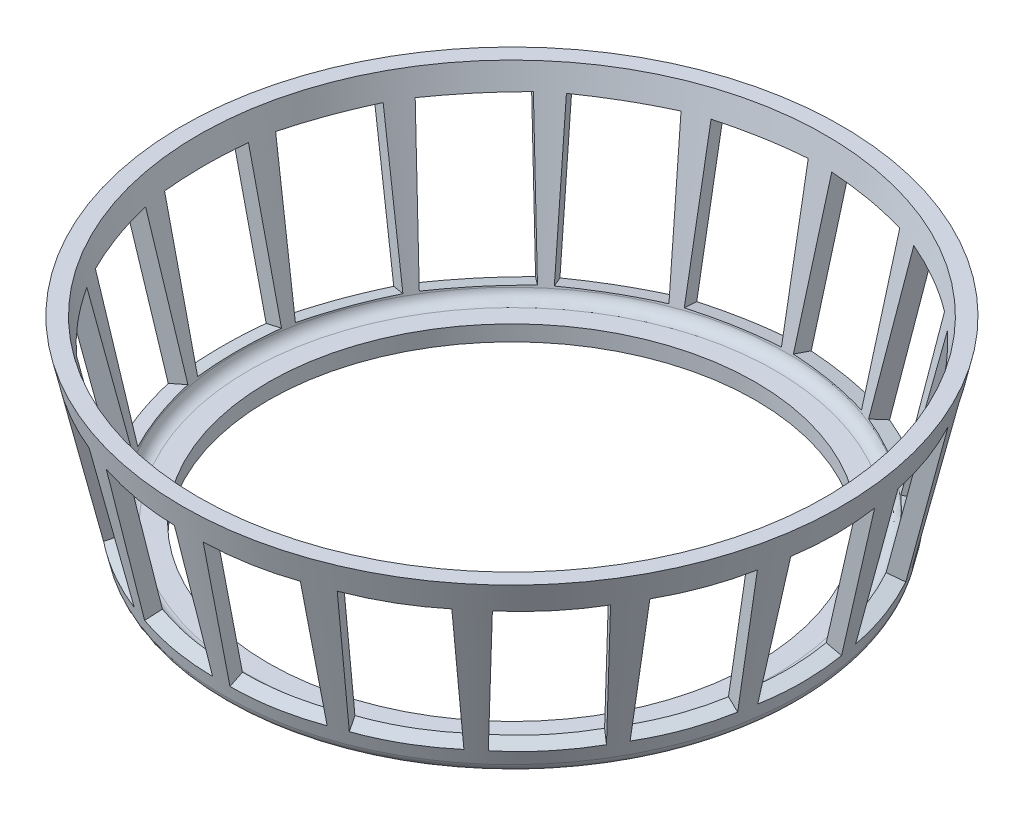
SolidWorks part; units mm, degrees
ref_plane "Front Plane" through (0, 0, 0) normal (0, 0, 1) x (1, 0, 0)
ref_plane "Top Plane" through (0, 0, 0) normal (0, 1, 0) x (1, 0, 0)
ref_plane "Right Plane" through (0, 0, 0) normal (1, 0, 0) x (0, 0, -1)
sketch "Sketch1" plane through (0, 0, 0) normal (0, 0, 1) x (1, 0, 0)
  line L0 (0, 12.1772) -> (0, 0) construction
  line L1 (0, 0) -> (-23.8186, 0) construction
  line L2 (-27.5, 16.23) -> (-23.9952, 0.7788)
  line L3 (-23.02, 0) -> (-20.3186, 0)
  line L4 (-26.167, 16.23) -> (-22.9571, 2.0788)
  line L5 (-21.9819, 1.3) -> (-20.3186, 1.3)
  line L6 (-27.5, 16.23) -> (-26.167, 16.23)
  line L7 (-20.3186, 1.3) -> (-20.3186, 0)
  line L8 (-26.2322, 16.5176) -> (-22.7804, 1.3) construction
  line L9 (-22.7804, 1.3) -> (-20.3186, 1.3) construction
  arc A0 (-23.02, 0) -> (-23.9952, 0.7788) centre (-23.02, 1) cw
  arc A2 (-22.9571, 2.0788) -> (-21.9819, 1.3) centre (-21.9819, 2.3) ccw
  arc A3 (-22.7804, 1.3) -> (-22.7804, 1.3) centre (-22.7804, 1.3) cw construction
  dimension "D5" = 1
  dimension "D7" = 1
  dimension "D1" = 27.5
  dimension "D2" = 102.78
  dimension "D3" = 3.5
  dimension "D4" = 16.23
  dimension "D6" = 1.3
revolve "Revolve1" add sketch "Sketch1" angle 360 about L0
sketch "Sketch2" plane through (0, 0, 0) normal (0, 0, 1) x (1, 0, 0)
  line L0 (23.9952, 0.7788) -> (27.5, 16.23) construction
  line L1 (23.9952, 0.7788) -> (27.5, 16.23) construction
ref_plane "Plane1" through (22.6531, -5.1383, 0) normal (0.9752, -0.2212, 0) x (0.2212, 0.9752, 0)
sketch "Sketch3" plane through (22.6531, -5.1383, 0) normal (0.9752, -0.2212, 0) x (0.2212, 0.9752, 0)
  line L0 (0, 0) -> (35.6522, 0) construction
  line L1 (21.9112, 0) -> (21.9112, 15.884) construction
  line L2 (19.5612, 3.5) -> (7.2112, 3.5)
  line L3 (19.5612, 3.5) -> (19.5612, -3.5)
  line L4 (19.5612, -3.5) -> (7.2112, -3.5)
  line L5 (7.2112, 3.5) -> (7.2112, -3.5)
  ellipse E0 centre (15.8279, 0) end of major axis (15.8279, -27.5) minor radius 6.0832 construction
  dimension "D1" = 2.35
  dimension "D2" = 12.35
  dimension "D3" = 7
extrude "Cut-Extrude1" cut sketch "Sketch3" against normal blind 10 contours L2 L5 L4 L3
pattern_circular "CirPattern1" count 18 over 360 about axis through (0, 0, 0) along (0, 1, 0) of "Cut-Extrude1"
